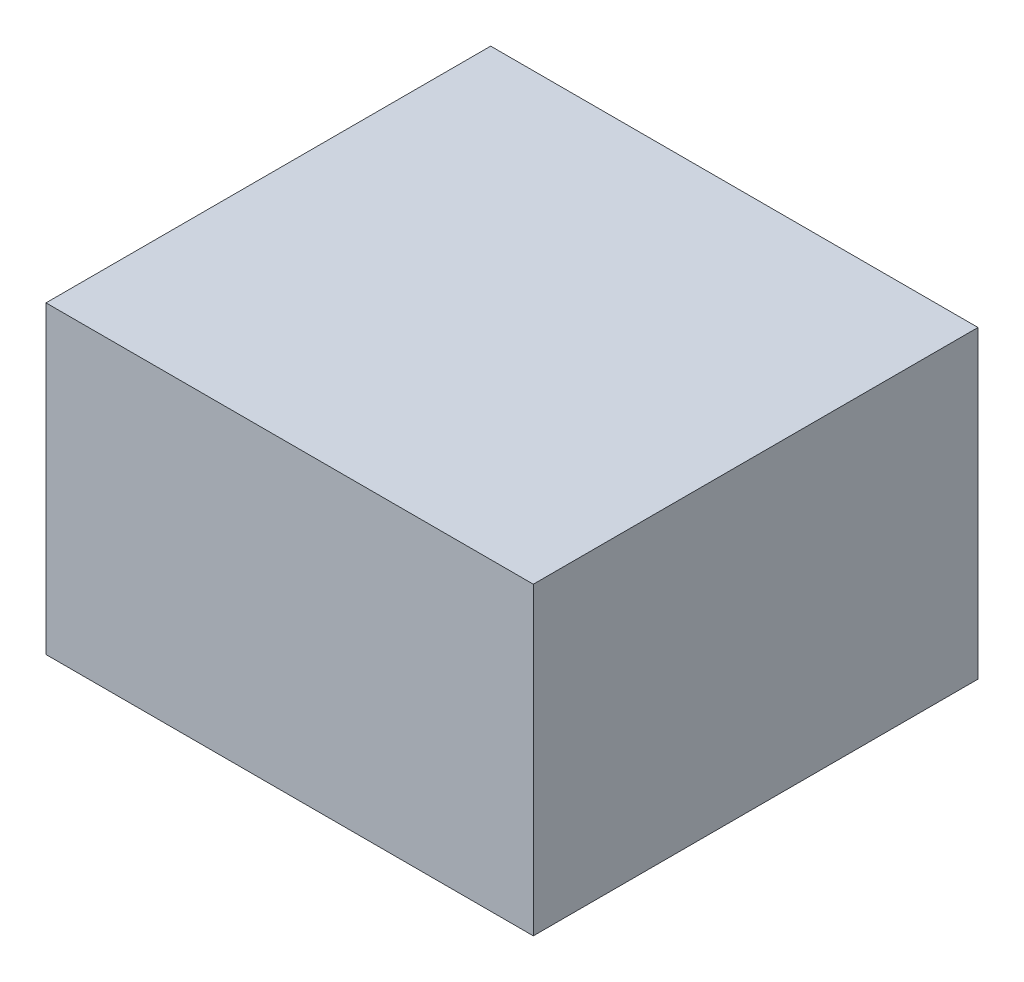
SolidWorks part; units mm, degrees
material "Rubber"
ref_plane "Front Plane" through (0, 0, 0) normal (0, 0, 1) x (1, 0, 0)
ref_plane "Top Plane" through (0, 0, 0) normal (0, 1, 0) x (1, 0, 0)
ref_plane "Right Plane" through (0, 0, 0) normal (1, 0, 0) x (0, 0, -1)
sketch "Sketch1" plane through (0, 0, 0) normal (0, 1, 0) x (1, 0, 0)
  line L1 (-6.8182, 5.4545) -> (9.1818, 5.4545)
  line L2 (-6.8182, 5.4545) -> (-6.8182, -9.1455)
  line L3 (-6.8182, -9.1455) -> (9.1818, -9.1455)
  line L4 (9.1818, 5.4545) -> (9.1818, -9.1455)
  dimension "D1" = 16
  dimension "D2" = 14.6
extrude "Boss-Extrude1" add sketch "Sketch1" along normal blind 10
